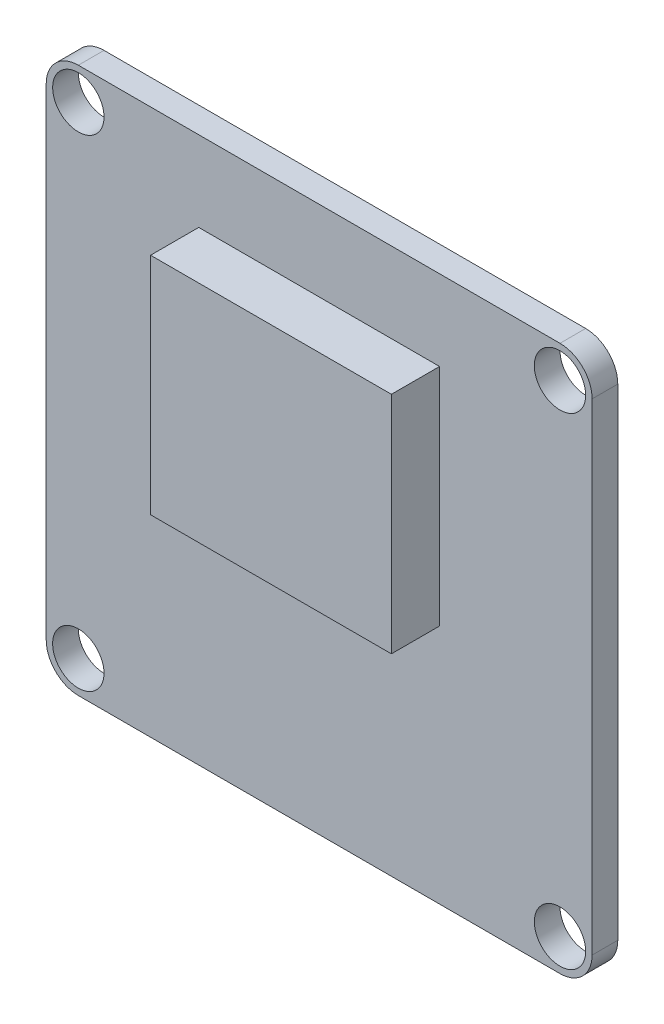
SolidWorks part; units mm, degrees
ref_plane "Front Plane" through (0, 0, 0) normal (0, 0, 1) x (1, 0, 0)
ref_plane "Top Plane" through (0, 0, 0) normal (0, 1, 0) x (1, 0, 0)
ref_plane "Right Plane" through (0, 0, 0) normal (1, 0, 0) x (0, 0, -1)
sketch "Sketch1" plane through (0, 0, 0) normal (0, 0, 1) x (1, 0, 0)
  line L0 (1.7643, 13.6116) -> (1.7643, -20.3884) construction
  line L1 (-13.2357, 13.6116) -> (16.7643, 13.6116)
  line L2 (-15.2357, 11.6116) -> (-15.2357, -18.3884)
  line L3 (-13.2357, -20.3884) -> (16.7643, -20.3884)
  line L4 (18.7643, 11.6116) -> (18.7643, -18.3884)
  line L5 (-15.2357, -3.3884) -> (18.7643, -3.3884) construction
  circle A0 centre (16.7643, 11.6116) radius 1.6
  arc A1 (-13.2357, 13.6116) -> (-15.2357, 11.6116) centre (-13.2357, 11.6116) ccw
  arc A2 (-15.2357, -18.3884) -> (-13.2357, -20.3884) centre (-13.2357, -18.3884) ccw
  arc A3 (16.7643, -20.3884) -> (18.7643, -18.3884) centre (16.7643, -18.3884) ccw
  arc A4 (16.7643, 13.6116) -> (18.7643, 11.6116) centre (16.7643, 11.6116) cw
  circle A5 centre (16.7643, -18.3884) radius 1.6
  circle A6 centre (-13.2357, 11.6116) radius 1.6
  circle A7 centre (-13.2357, -18.3884) radius 1.6
  point P12 (-15.2357, 13.6116)
  point P17 (18.7643, -20.3884)
  point P20 (18.7643, 13.6116)
  dimension "D3" = 2
extrude "Boss-Extrude1" add sketch "Sketch1" along normal blind 1.6
sketch "Sketch3" plane through (0, 0, 1.6) normal (0, 0, 1) x (1, 0, 0)
  line L0 (1.7643, 13.6116) -> (1.7643, -61.4053) construction
  line L1 (16.7643, 13.6116) -> (-13.2357, 13.6116) construction
  line L2 (1.7643, 13.6116) -> (22.1688, 13.6116) construction
  line L3 (9.2643, 8.6116) -> (-5.7357, 8.6116)
  line L4 (9.2643, 8.6116) -> (9.2643, -5.3884)
  line L5 (9.2643, -5.3884) -> (-5.7357, -5.3884)
  line L6 (-5.7357, 8.6116) -> (-5.7357, -5.3884)
  ellipse E0 centre (1.7643, -59.2922) end of major axis (-3.2357, -59.2922) minor radius 2.1131 construction
  point P14 (0, 0)
  dimension "D1" = 14
  dimension "D2" = 15
  dimension "D3" = 7.5
  dimension "D4" = 5
extrude "Boss-Extrude2" add sketch "Sketch3" along normal blind 3
